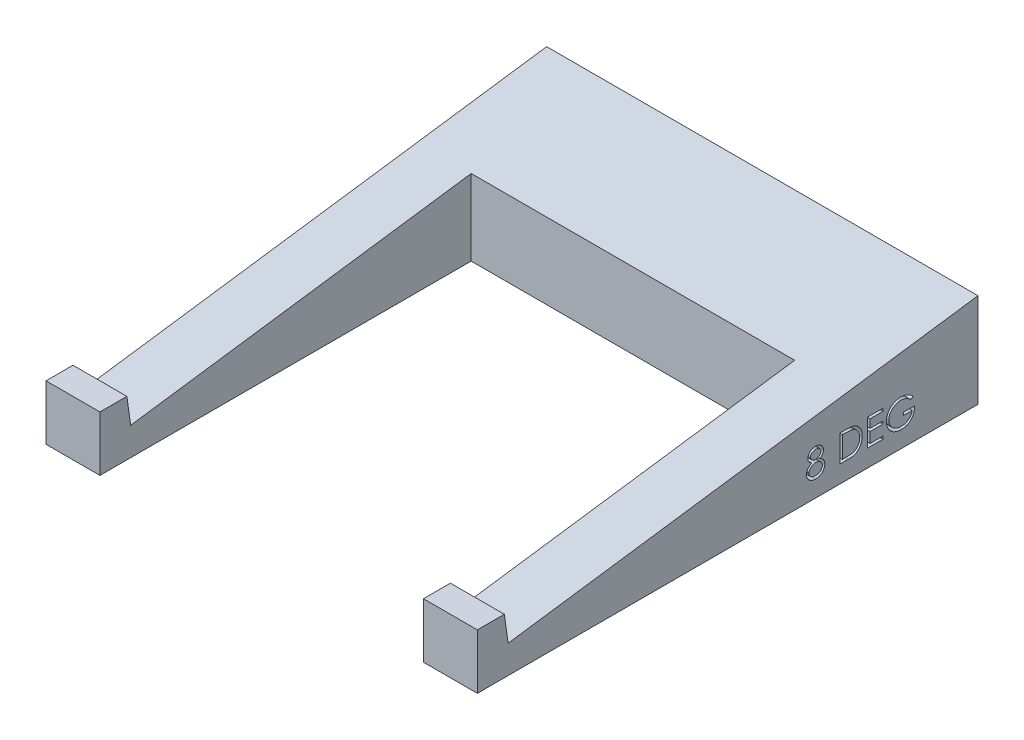
SolidWorks part; units mm, degrees
ref_plane "Front Plane" through (0, 0, 0) normal (0, 0, 1) x (1, 0, 0)
ref_plane "Top Plane" through (0, 0, 0) normal (0, 1, 0) x (1, 0, 0)
ref_plane "Right Plane" through (0, 0, 0) normal (1, 0, 0) x (0, 0, -1)
sketch "Sketch1" plane through (0, 0, 0) normal (1, 0, 0) x (0, 0, -1)
  line L1 (11.9888, 15.748) -> (11.9888, 26.827)
  line L2 (11.9888, 26.827) -> (6.9582, 26.12)
  line L4 (0, 19.05) -> (11.9888, 19.05) construction
  line L5 (6.9582, 26.12) -> (-43.3474, 19.05) construction
  line L6 (-43.3474, 19.05) -> (0, 19.05) construction
  line L7 (-43.3474, 19.05) -> (6.9582, 26.12)
  line L8 (-43.3474, 19.05) -> (-43.7936, 22.225)
  line L9 (-43.7936, 22.225) -> (-46.9686, 22.225)
  line L10 (-46.9686, 22.225) -> (-46.9686, 15.748)
  line L11 (-46.9686, 15.748) -> (11.9888, 15.748)
  point P0 (4.2033, 11.6698)
  point P7 (0, 0)
  point P13 (0, 0)
  point P16 (0, 0)
  dimension "D1" = 8
  dimension "D2" = 11.9888
  dimension "D3" = 55.88
  dimension "D4" = 15.748
  dimension "D5" = 3.175
  dimension "D6" = 3.175
  dimension "D7" = 3.302
  dimension "D8" = 50.8
  dimension "D9" = 11.9888
extrude "Boss-Extrude1" add sketch "Sketch1" along normal blind 50.8
sketch "Sketch2" [suppressed] plane through (0, 0, 0) normal (0, 0, 1) x (1, 0, 0)
  line L0 (50.8, 0) -> (0, 0) construction
  line L1 (19.05, 19.05) -> (31.75, 19.05)
  line L2 (19.05, 19.05) -> (19.05, 0)
  line L3 (19.05, 0) -> (31.75, 0)
  line L4 (31.75, 19.05) -> (31.75, 0)
  line L5 (19.05, 19.05) -> (31.75, 0) construction
  line L6 (19.05, 0) -> (31.75, 19.05) construction
  line L8 (0, 0) -> (12.7, 0)
  line L9 (0, 0) -> (0, 19.05)
  line L10 (0, 19.05) -> (12.7, 19.05)
  line L11 (12.7, 0) -> (12.7, 19.05)
  line L12 (50.8, 0) -> (38.1, 0)
  line L13 (50.8, 0) -> (50.8, 19.05)
  line L14 (50.8, 19.05) -> (38.1, 19.05)
  line L15 (38.1, 0) -> (38.1, 19.05)
  point P0 (25.4, 9.525)
  point P7 (25.4, 0)
  dimension "D1" = 19.05
  dimension "D2" = 12.7
  dimension "D3" = 12.7
  dimension "D4" = 12.7
extrude "Cut-Extrude1" [suppressed] cut sketch "Sketch2" against normal through all
hole_wizard "M3 Clearance Hole1" [suppressed] positions "Sketch3" profile "Sketch4" hole size "M3" standard "ANSI Metric"
sketch "Sketch3" [suppressed] plane through (50.8, 0, 0) normal (1, 0, 0) x (0, 0, -1)
  line L0 (11.9888, 19.05) -> (0, 19.05) construction
  line L2 (11.9888, 19.05) -> (11.9888, 26.827) construction
  point P0 (5.9944, 13.0556)
  dimension "D1" = 5.9944
  dimension "D2" = 5.9944
sketch "Sketch4" plane through (50.8, 13.0556, -5.9944) normal (0, 1, 0) x (0, 0, -1)
  line L0 (0, 0) -> (0, 50.8)
  line L1 (0, 50.8) -> (1.8, 50.8)
  line L2 (1.8, 50.8) -> (1.8, 0)
  line L5 (1.8, 0) -> (0, 0)
  line L11 (0, -6.35) -> (0, 107.95) construction
  dimension "Thru Hole Dia." = 3.6
  dimension "Thru Hole Depth" = 50.8
sketch "Sketch5" plane through (0, 0, 0) normal (0, 1, 0) x (1, 0, 0)
  line L0 (50.8, -46.9686) -> (0, -46.9686) construction
  line L1 (44.45, -46.9686) -> (6.35, -46.9686)
  line L2 (44.45, -46.9686) -> (44.45, -3.2512)
  line L3 (44.45, -3.2512) -> (6.35, -3.2512)
  line L4 (6.35, -46.9686) -> (6.35, -3.2512)
  line L5 (0, -46.9686) -> (0, 11.9888) construction
  line L6 (50.8, 11.9888) -> (0, 11.9888) construction
  dimension "D1" = 38.1
  dimension "D2" = 6.35
  dimension "D3" = 15.24
extrude "Cut-Extrude2" cut sketch "Sketch5" along normal through all
sketch "Sketch7" plane through (50.8, 0, 0) normal (1, 0, 0) x (0, 0, -1)
  line L1 (-46.9686, 15.748) -> (11.9888, 15.748) construction
  line L2 (11.9888, 15.748) -> (11.9888, 26.827) construction
  text T0 "8 DEG"
  dimension "D1" = 2.032
  dimension "D2" = 20.32
extrude "Cut-Extrude4" cut sketch "Sketch7" against normal blind 2.54
